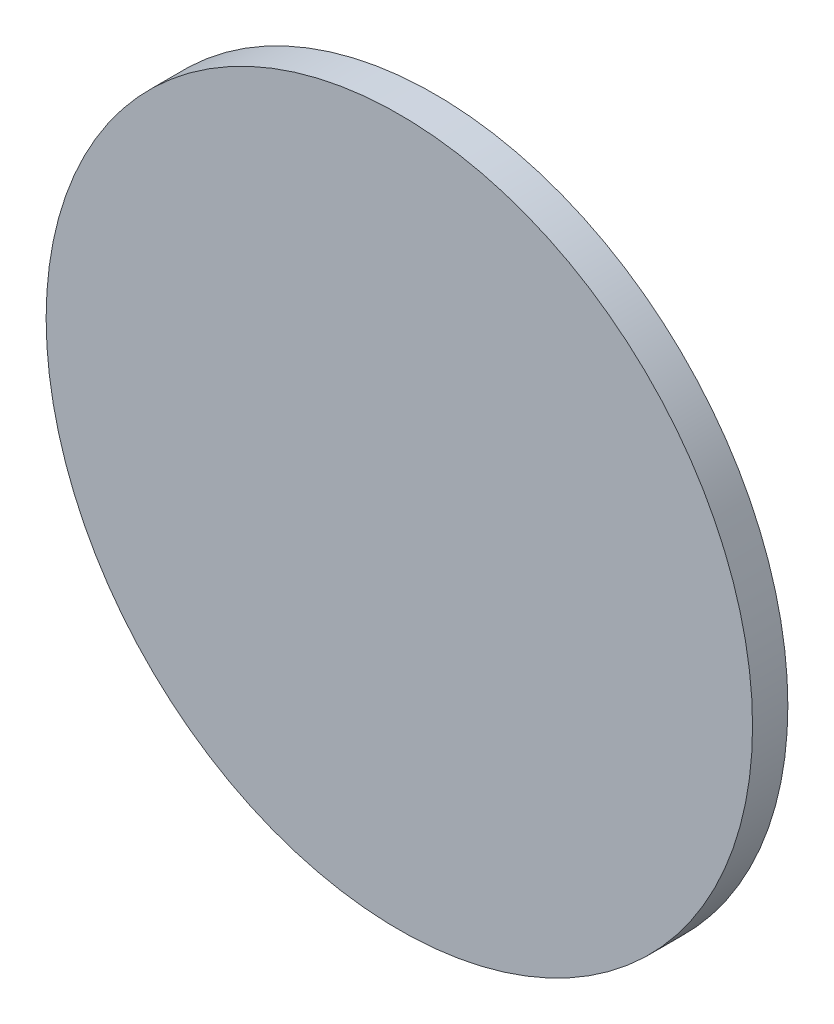
SolidWorks part; units mm, degrees
ref_plane "正面" through (0, 0, 0) normal (0, 0, 1) x (1, 0, 0)
ref_plane "平面" through (0, 0, 0) normal (0, 1, 0) x (1, 0, 0)
ref_plane "右側面" through (0, 0, 0) normal (1, 0, 0) x (0, 0, -1)
sketch "ｽｹｯﾁ1" plane through (0, 0, 0) normal (0, 0, 1) x (1, 0, 0)
  circle A0 centre (0, 0) radius 100
  dimension "D1" = 200
extrude "ﾎﾞｽ - 押し出し1" add sketch "ｽｹｯﾁ1" along normal blind 10
